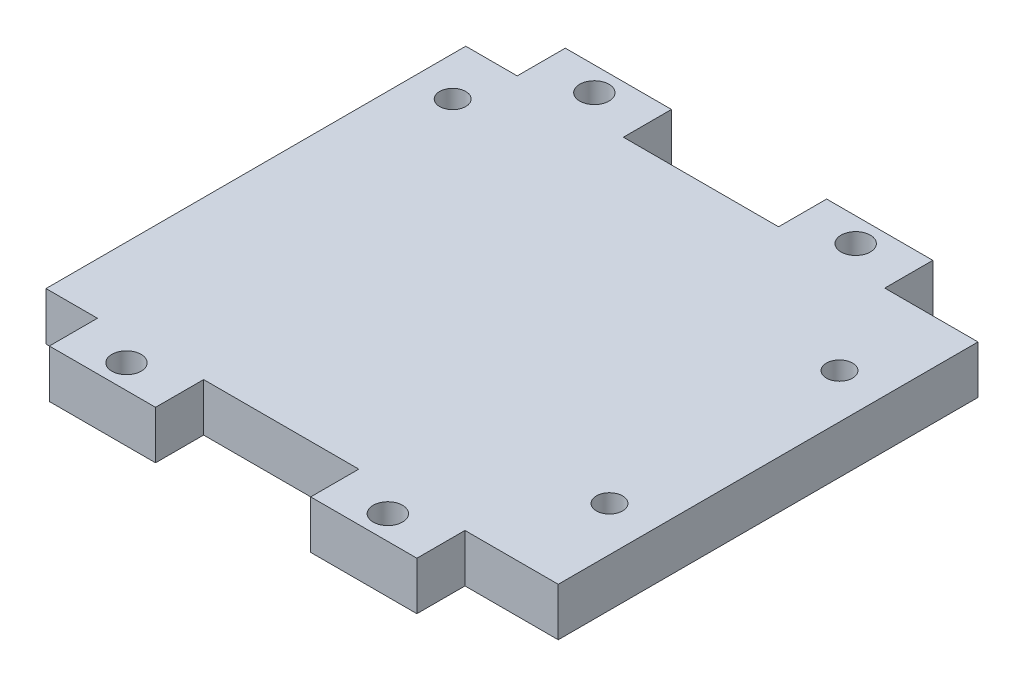
SolidWorks part; units mm, degrees
ref_plane "Front Plane" through (0, 0, 0) normal (0, 0, 1) x (1, 0, 0)
ref_plane "Top Plane" through (0, 0, 0) normal (0, 1, 0) x (1, 0, 0)
ref_plane "Right Plane" through (0, 0, 0) normal (1, 0, 0) x (0, 0, -1)
sketch "Sketch1" plane through (0, 0, 0) normal (0, 1, 0) x (1, 0, 0)
  line L0 (-28.575, 25.4975) -> (-22.325, 25.4975)
  line L1 (22.325, -25.4975) -> (28.575, -25.4975)
  line L2 (28.575, -25.4975) -> (28.575, 25.4975)
  line L3 (22.325, 31.3395) -> (9.425, 31.3395)
  line L4 (-28.575, -25.4975) -> (-28.575, 25.4975)
  line L5 (0, 31.3395) -> (0, -31.3395) construction
  line L6 (28.575, 0) -> (-28.575, 0) construction
  line L7 (-28.575, -25.4975) -> (-22.325, -25.4975)
  line L8 (-9.425, 25.4975) -> (9.425, 25.4975)
  line L9 (22.325, 25.4975) -> (22.325, 31.3395)
  line L10 (-22.325, 25.4975) -> (-22.325, 31.3395)
  line L11 (-22.325, 31.3395) -> (-9.425, 31.3395)
  line L12 (-9.425, 25.4975) -> (-9.425, 31.3395)
  line L13 (-22.325, 25.4975) -> (-9.425, 31.3395) construction
  line L14 (-22.325, 31.3395) -> (-9.425, 25.4975) construction
  line L15 (9.425, 25.4975) -> (9.425, 31.3395)
  line L16 (-9.425, 31.3395) -> (-22.325, 31.3395)
  line L17 (22.325, 25.4975) -> (28.575, 25.4975)
  line L18 (-22.325, -31.3395) -> (-9.425, -25.4975) construction
  line L19 (-22.325, -25.4975) -> (-9.425, -31.3395) construction
  line L20 (-9.425, -31.3395) -> (-22.325, -31.3395)
  line L21 (9.425, -25.4975) -> (9.425, -31.3395)
  line L22 (-9.425, -25.4975) -> (-9.425, -31.3395)
  line L23 (-22.325, -31.3395) -> (-9.425, -31.3395)
  line L24 (-22.325, -25.4975) -> (-22.325, -31.3395)
  line L25 (22.325, -25.4975) -> (22.325, -31.3395)
  line L26 (-9.425, -25.4975) -> (9.425, -25.4975)
  line L27 (22.325, -31.3395) -> (9.425, -31.3395)
  point P0 (0, 0)
  point P12 (-15.875, 28.4185)
  point P29 (-15.875, -28.4185)
  dimension "D3" = 5.842
  dimension "D4" = 12.9
  dimension "D5" = 15.875
extrude "Boss-Extrude1" add sketch "Sketch1" along normal blind 5.842 contours L27 L25 L1 L2 L17 L9 L3 L15 L8 L12 L11 L10 L0 L4 L7 L24 L20 L22 L26 L21
sketch "Sketch2" plane through (0, 5.842, 0) normal (0, 1, 0) x (1, 0, 0)
  line L0 (-15.875, 31.3395) -> (-15.875, -31.3395) construction
  line L1 (-22.325, 31.3395) -> (-9.425, 31.3395) construction
  line L2 (-9.425, -31.3395) -> (-22.325, -31.3395) construction
  line L3 (-9.425, -28.4185) -> (-22.325, -28.4185) construction
  line L4 (-9.425, -25.4975) -> (-9.425, -31.3395) construction
  line L5 (-22.325, -25.4975) -> (-22.325, -31.3395) construction
  line L6 (-9.425, 28.4185) -> (-22.325, 28.4185) construction
  line L7 (-9.425, 25.4975) -> (-9.425, 31.3395) construction
  line L8 (-22.325, 25.4975) -> (-22.325, 31.3395) construction
  line L9 (0, 25.4975) -> (0, -25.4975) construction
  line L10 (-9.425, 25.4975) -> (9.425, 25.4975) construction
  line L11 (-9.425, -25.4975) -> (9.425, -25.4975) construction
  circle A0 centre (-15.875, 28.4185) radius 1.778
  circle A1 centre (-15.875, -28.4185) radius 1.778
  circle A2 centre (15.875, 28.4185) radius 1.778
  circle A3 centre (15.875, -28.4185) radius 1.778
extrude "Cut-Extrude1" cut sketch "Sketch2" against normal through all
sketch "Sketch3" plane through (0, 5.842, 0) normal (0, 1, 0) x (1, 0, 0)
  line L1 (28.575, 25.4975) -> (33.655, 25.4975)
  line L2 (28.575, 25.4975) -> (28.575, -25.4975)
  line L3 (28.575, -25.4975) -> (33.655, -25.4975)
  line L4 (33.655, 25.4975) -> (33.655, -25.4975)
  line L5 (28.575, 25.4975) -> (33.655, -25.4975) construction
  line L6 (28.575, -25.4975) -> (33.655, 25.4975) construction
  point P4 (31.115, 0)
  dimension "D1" = 5.08
extrude "Boss-Extrude2" add sketch "Sketch3" against normal up to surface (5.842 mm away) up to face at (15.875, 0, 26.6405)
sketch "Sketch4" plane through (0, 0, 0) normal (0, -1, 0) x (-1, 0, 0)
  line L0 (28.575, 25.4975) -> (22.325, 25.4975) construction
  line L1 (28.575, -25.4975) -> (28.575, 25.4975) construction
  line L2 (-28.2575, 25.4975) -> (-28.2575, -25.4975) construction
  line L3 (-22.325, 25.4975) -> (-33.655, 25.4975) construction
  line L4 (-22.325, -25.4975) -> (-33.655, -25.4975) construction
  circle A0 centre (23.8125, 19.1475) radius 1.5875
  circle A1 centre (-28.2575, 14.0675) radius 1.5875
  circle A2 centre (-28.2575, -13.8725) radius 1.5875
  dimension "D1" = 6.35
  dimension "D3" = 3.175
  dimension "D4" = 3.175
  dimension "D2" = 4.7625
  dimension "D5" = 52.07
  dimension "D6" = 5.08
  dimension "D7" = 27.94
extrude "Cut-Extrude2" cut sketch "Sketch4" against normal through all
